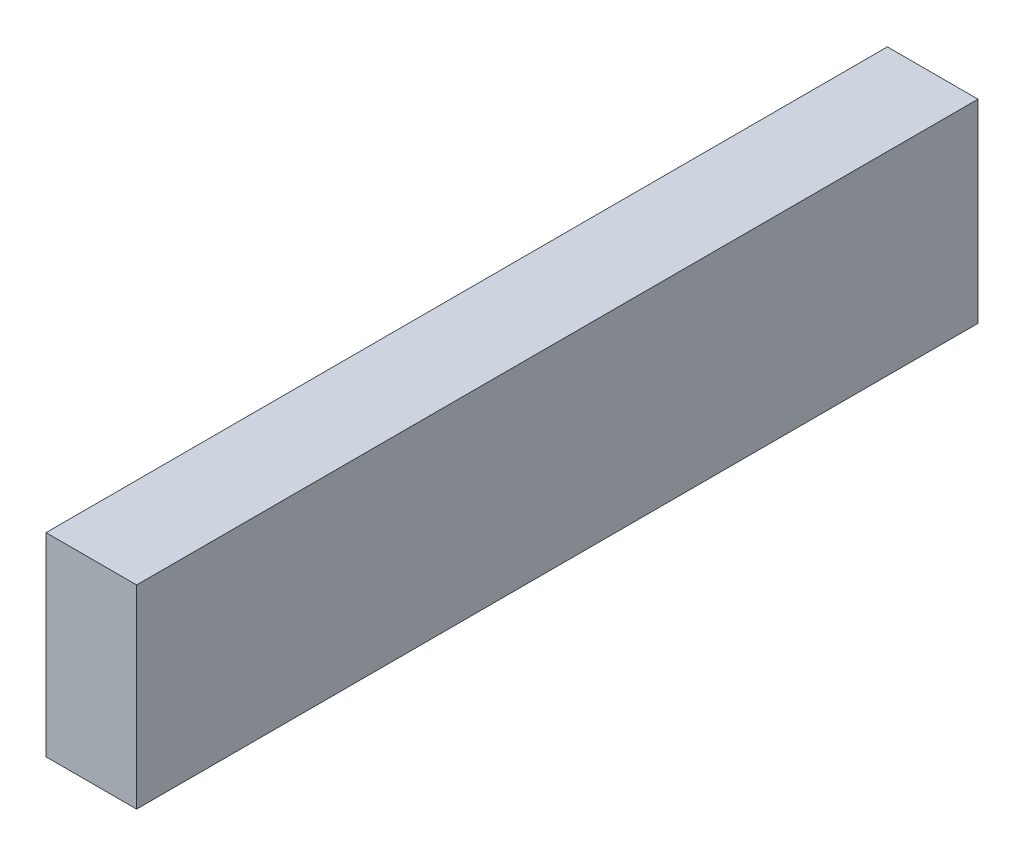
SolidWorks part; units mm, degrees
ref_plane "Front Plane" through (0, 0, 0) normal (0, 0, 1) x (1, 0, 0)
ref_plane "Top Plane" through (0, 0, 0) normal (0, 1, 0) x (1, 0, 0)
ref_plane "Right Plane" through (0, 0, 0) normal (1, 0, 0) x (0, 0, -1)
sketch "Sketch1" plane through (0, 0, 0) normal (0, 0, 1) x (1, 0, 0)
  line L1 (-54.6429, 20.0893) -> (-47.6429, 20.0893)
  line L2 (-54.6429, 20.0893) -> (-54.6429, 5.0893)
  line L3 (-54.6429, 5.0893) -> (-47.6429, 5.0893)
  line L4 (-47.6429, 20.0893) -> (-47.6429, 5.0893)
  line L5 (-54.6429, 20.0893) -> (-47.6429, 5.0893) construction
  line L6 (-54.6429, 5.0893) -> (-47.6429, 20.0893) construction
  point P0 (-51.1429, 12.5893)
  dimension "D1" = 15
  dimension "D2" = 7
extrude "Boss-Extrude1" add sketch "Sketch1" along normal blind 65
